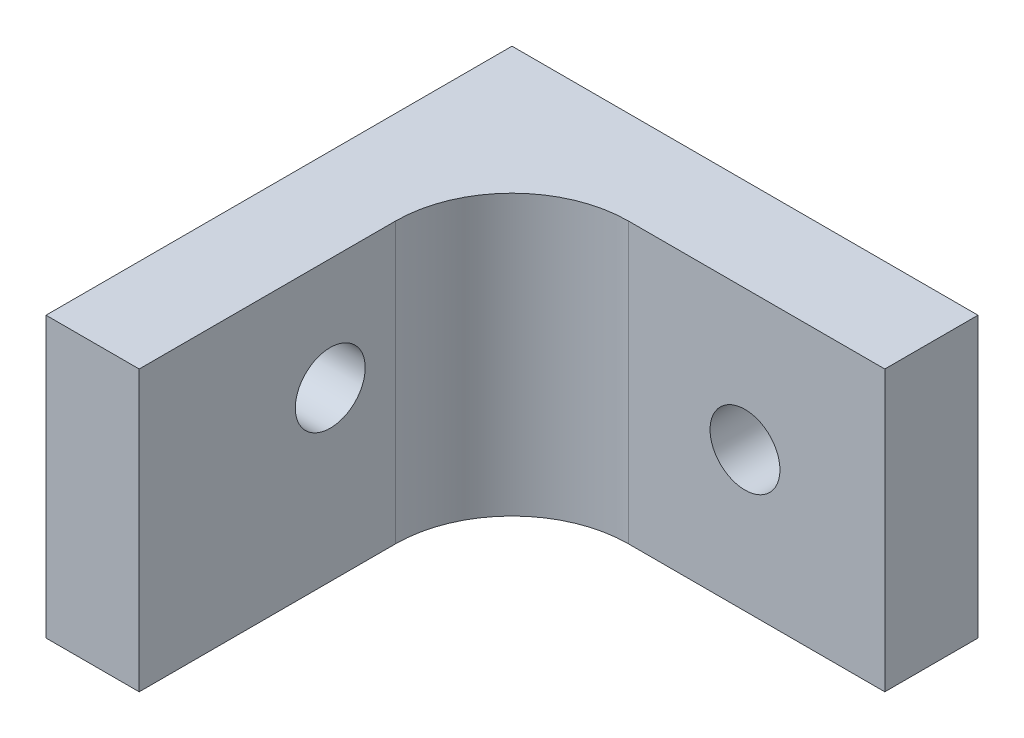
SolidWorks part; units mm, degrees
ref_plane "Front Plane" through (0, 0, 0) normal (0, 0, 1) x (1, 0, 0)
ref_plane "Top Plane" through (0, 0, 0) normal (0, 1, 0) x (1, 0, 0)
ref_plane "Right Plane" through (0, 0, 0) normal (1, 0, 0) x (0, 0, -1)
sketch "Sketch1" plane through (0, 0, 0) normal (0, 0, 1) x (1, 0, 0)
  line L0 (-3, -6) -> (-3, -3) construction
  line L1 (0, -6) -> (-10, -6)
  line L2 (0, -6) -> (0, 0)
  line L3 (0, 0) -> (-10, 0)
  line L4 (-10, -6) -> (-10, 0)
  line L5 (-3, -3) -> (0, -3) construction
  circle A0 centre (-3, -3) radius 0.75
  dimension "D5" = 1.5
  dimension "D1" = 10
  dimension "D2" = 6
  dimension "D3" = 3
  dimension "D4" = 3
extrude "Boss-Extrude1" add sketch "Sketch1" along normal blind 2
sketch "Sketch2" plane through (-10, 0, 0) normal (-1, 0, 0) x (0, 0, 1)
  line L0 (5.9, 0) -> (5.9, -2.4) construction
  line L1 (0, 0) -> (10, 0)
  line L2 (0, 0) -> (0, -6)
  line L3 (0, -6) -> (10, -6)
  line L4 (10, 0) -> (10, -6)
  line L5 (5.9, -2.4) -> (10, -2.4) construction
  circle A2 centre (5.9, -2.4) radius 0.75
  point P7 (5.9, -2.4)
  dimension "D5" = 1.5
  dimension "D1" = 6
  dimension "D2" = 10
  dimension "D3" = 2.4
  dimension "D4" = 4.1
extrude "Boss-Extrude2" add sketch "Sketch2" against normal blind 2
fillet "Fillet2" radius 2.5 1 edges at (-8, -3, 2)
